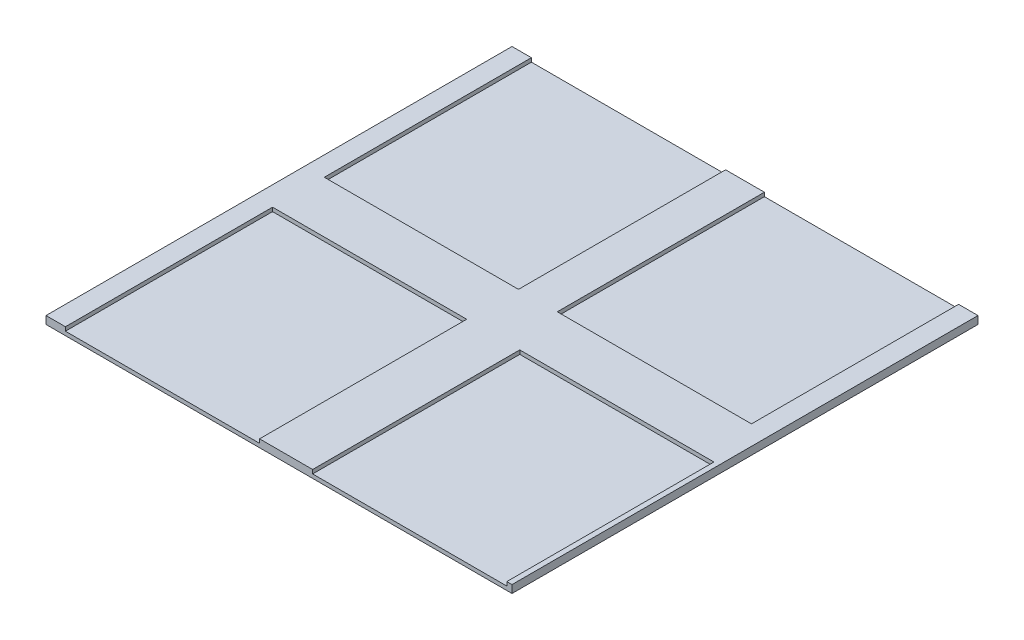
SolidWorks part; units mm, degrees
ref_plane "前视基准面" through (0, 0, 0) normal (0, 0, 1) x (1, 0, 0)
ref_plane "上视基准面" through (0, 0, 0) normal (0, 1, 0) x (1, 0, 0)
ref_plane "右视基准面" through (0, 0, 0) normal (1, 0, 0) x (0, 0, -1)
sketch "草图1" plane through (0, 0, 0) normal (0, 1, 0) x (1, 0, 0)
  line L9 (-180, 180) -> (180, 180)
  line L10 (-180, 180) -> (-180, -180)
  line L11 (-180, -180) -> (180, -180)
  line L12 (180, 180) -> (180, -180)
  line L13 (-180, 180) -> (180, -180) construction
  line L14 (-180, -180) -> (180, 180) construction
  point P0 (0, 0)
  dimension "D1" = 360
extrude "凸台-拉伸1" add sketch "草图1" along normal blind 6
sketch "草图2" plane through (0, 6, 0) normal (0, 1, 0) x (1, 0, 0)
  line L0 (-160, -20) -> (-20, -20)
  line L7 (-180, 0) -> (0, 0) construction
  line L8 (0, 180) -> (0, -180) construction
  line L9 (-180, 180) -> (-180, -180) construction
  line L17 (-180, -180) -> (180, -180) construction
  line L18 (-90, 90) -> (-90, -90) construction
  line L36 (-160, -20) -> (-160, -160)
  line L37 (-160, -160) -> (-20, -160)
  line L39 (-160, -20) -> (-20, -160) construction
  line L48 (-160, -160) -> (-2.156, -2.156) construction
  line L66 (-20, -20) -> (-20, -160)
  line L67 (160, -160) -> (2.156, -2.156) construction
  line L72 (160, -20) -> (20, -160) construction
  line L73 (90, 90) -> (90, -90) construction
  line L78 (20, -20) -> (20, -160)
  line L79 (160, -160) -> (20, -160)
  line L80 (160, -20) -> (160, -160)
  line L81 (160, -20) -> (20, -20)
  line L82 (160, 20) -> (20, 160) construction
  line L83 (160, 160) -> (2.156, 2.156) construction
  line L84 (-160, 160) -> (-2.156, 2.156) construction
  line L85 (-160, 20) -> (-20, 160) construction
  line L86 (160, 20) -> (20, 20)
  line L87 (160, 20) -> (160, 160)
  line L88 (160, 160) -> (20, 160)
  line L89 (20, 20) -> (20, 160)
  line L90 (-20, 20) -> (-20, 160)
  line L91 (-160, 160) -> (-20, 160)
  line L92 (-160, 20) -> (-160, 160)
  line L93 (-160, 20) -> (-20, 20)
  point P22 (90, 0)
  point P31 (-90, 0)
  dimension "D4" = 40
  dimension "D1" = 40
  dimension "D2" = 140
  dimension "D3" = 140
extrude "切除-拉伸1" cut sketch "草图2" against normal blind 3
sketch "草图7" plane through (0, 3, 0) normal (0, 1, 0) x (1, 0, 0)
  line L0 (-121.6814, 0) -> (0, 0) construction
  line L18 (0, 82.317) -> (0, -82.317) construction
  line L19 (160, -20) -> (160, -189.1496)
  line L20 (-20, -20) -> (-160, -20)
  line L21 (-20, -20) -> (-20, -189.1496)
  line L22 (-20, -189.1496) -> (-160, -189.1496)
  line L23 (-160, -20) -> (-160, -189.1496)
  line L24 (20, -189.1496) -> (160, -189.1496)
  line L25 (20, -20) -> (20, -189.1496)
  line L26 (20, -20) -> (160, -20)
  line L27 (20, 20) -> (160, 20)
  line L28 (20, 20) -> (20, 189.1496)
  line L29 (20, 189.1496) -> (160, 189.1496)
  line L30 (-160, 20) -> (-160, 189.1496)
  line L31 (-20, 189.1496) -> (-160, 189.1496)
  line L32 (-20, 20) -> (-20, 189.1496)
  line L33 (-20, 20) -> (-160, 20)
  line L34 (160, 20) -> (160, 189.1496)
  dimension "D1" = 140
extrude "切除-拉伸2" cut sketch "草图7" along normal blind 110
sketch "草图4" plane through (0, 0, 0) normal (0, -1, 0) x (1, 0, 0)
  circle A0 centre (0, 0) radius 42.2122
extrude "凸台-拉伸2" add sketch "草图4" along normal blind 1
sketch "草图10" plane through (0, 6, 0) normal (0, 1, 0) x (1, 0, 0)
  line L0 (160, -20) -> (166, -20)
  line L3 (166, -180) -> (160, -180)
  line L4 (160, -180) -> (160, -20)
  line L5 (166, -20) -> (166, -180)
  dimension "D1" = 6
extrude "切除-拉伸3" cut sketch "草图10" against normal up to surface (3 mm away) up to face at (90, 3, 100)
sketch "草图11" plane through (0, 6, 0) normal (0, 1, 0) x (1, 0, 0)
  line L0 (166, -180) -> (20, -180) construction
  line L5 (20, -20) -> (26, -20)
  line L6 (20, -20) -> (20, -180)
  line L7 (20, -180) -> (26, -180)
  line L8 (26, -20) -> (26, -180)
  dimension "D1" = 6
extrude "凸台-拉伸3" add sketch "草图11" against normal up to surface (3 mm away) up to face at (93, 3, 100)
sketch "草图12" plane through (0, 6, 0) normal (0, 1, 0) x (1, 0, 0)
  line L0 (166, -180) -> (166, -20) construction
  line L1 (166, -20) -> (180, -20)
  line L2 (166, -20) -> (166, -180)
  line L3 (166, -180) -> (180, -180)
  line L4 (180, -20) -> (180, -180)
  line L5 (166, -180) -> (166, -20) construction
extrude "切除-拉伸4" cut sketch "草图12" against normal up to surface (3 mm away) up to face at (96, 3, 100)
sketch "草图13" plane through (0, 3, 0) normal (0, 1, 0) x (1, 0, 0)
  line L0 (180, -180) -> (26, -180) construction
  line L4 (40, -20) -> (40, -180)
  line L6 (26, -20) -> (40, -20)
  line L7 (26, -20) -> (26, -180)
  line L8 (26, -180) -> (40, -180)
  line L9 (40, -20) -> (40, -180)
  line M3 (180, -20) -> (26, -20)
  line M4 (26, -20) -> (26, -180)
  line M5 (26, -180) -> (180, -180)
extrude "凸台-拉伸4" add sketch "草图13" along normal up to surface (3 mm away) contours L4 M3 M4 M5 up to face at (-17.1111, 6, -20)
sketch "草图14" plane through (0, 3, 0) normal (0, 1, 0) x (1, 0, 0)
  line L0 (180, -180) -> (40, -180) construction
  line L1 (180, -20) -> (176, -20)
  line L2 (180, -20) -> (180, -180)
  line L3 (180, -180) -> (176, -180)
  line L4 (176, -20) -> (176, -180)
  dimension "D1" = 4
extrude "凸台-拉伸5" add sketch "草图14" along normal up to surface (3 mm away) up to face at (-15.5556, 6, -20)
sketch "草图15" plane through (0, 6, 0) normal (0, 1, 0) x (1, 0, 0)
  line L0 (-20, -180) -> (40, -180) construction
  line L1 (40, -20) -> (36, -20)
  line L2 (40, -20) -> (40, -180)
  line L3 (40, -180) -> (36, -180)
  line L4 (36, -20) -> (36, -180)
  dimension "D1" = 4
extrude "切除-拉伸5" cut sketch "草图15" against normal up to surface (3 mm away) up to face at (108, 3, 100)
sketch "草图16" plane through (0, 6, 0) normal (0, 1, 0) x (1, 0, 0)
  line L2 (-15, -170) -> (-15, -20)
  line L3 (-15, -20) -> (-165, -20)
  line L4 (-165, -170) -> (-165, -20)
  line L5 (-15, -170) -> (-165, -20) construction
  line L6 (-15, -20) -> (-165, -170) construction
  line L7 (-90, -20) -> (-90, -52.5331) construction
  line L8 (-20, -20) -> (-160, -20) construction
  line L10 (-117.6333, 0) -> (0, 0) construction
  line L11 (-90, 20) -> (-90, 52.5331) construction
  line L12 (-15, 20) -> (-165, 170) construction
  line L13 (-15, 170) -> (-165, 20) construction
  line L14 (-165, 170) -> (-165, 20)
  line L15 (-15, 20) -> (-165, 20)
  line L16 (-15, 170) -> (-15, 20)
  line L18 (0, 109.5189) -> (0, 0) construction
  line L20 (-165, -170) -> (-165, -206.2013)
  line L21 (-165, -206.2013) -> (-15, -206.2013)
  line L22 (-15, -170) -> (-15, -206.2013)
  line L24 (-165, 170) -> (-165, 194.4237)
  line L25 (-165, 194.4237) -> (-15, 194.4237)
  line L26 (-15, 170) -> (-15, 194.4237)
  line L27 (15, 170) -> (165, 20) construction
  line L28 (15, 20) -> (165, 170) construction
  line L29 (90, 20) -> (90, 52.5331) construction
  line L30 (15, 170) -> (15, 194.4237)
  line L31 (165, 194.4237) -> (15, 194.4237)
  line L32 (165, 170) -> (165, 194.4237)
  line L33 (15, 170) -> (15, 20)
  line L34 (15, 20) -> (165, 20)
  line L35 (165, 170) -> (165, 20)
  point P0 (-90, -95)
  point P18 (-90, 95)
  point P32 (90, 95)
  dimension "D1" = 150
  dimension "D2" = 0
  dimension "D3" = 0
extrude "切除-拉伸6" cut sketch "草图16" against normal up to surface (3 mm away) up to face at (-90, 3, -100)
sketch "草图17" plane through (0, 6, 0) normal (0, 1, 0) x (1, 0, 0)
  line L1 (176, -20) -> (26, -20)
  line L2 (176, -20) -> (176, -185.6021)
  line L3 (176, -185.6021) -> (26, -185.6021)
  line L4 (26, -20) -> (26, -185.6021)
  dimension "D1" = 150
extrude "切除-拉伸7" cut sketch "草图17" against normal up to surface (3 mm away) up to face at (106, 3, 100)
